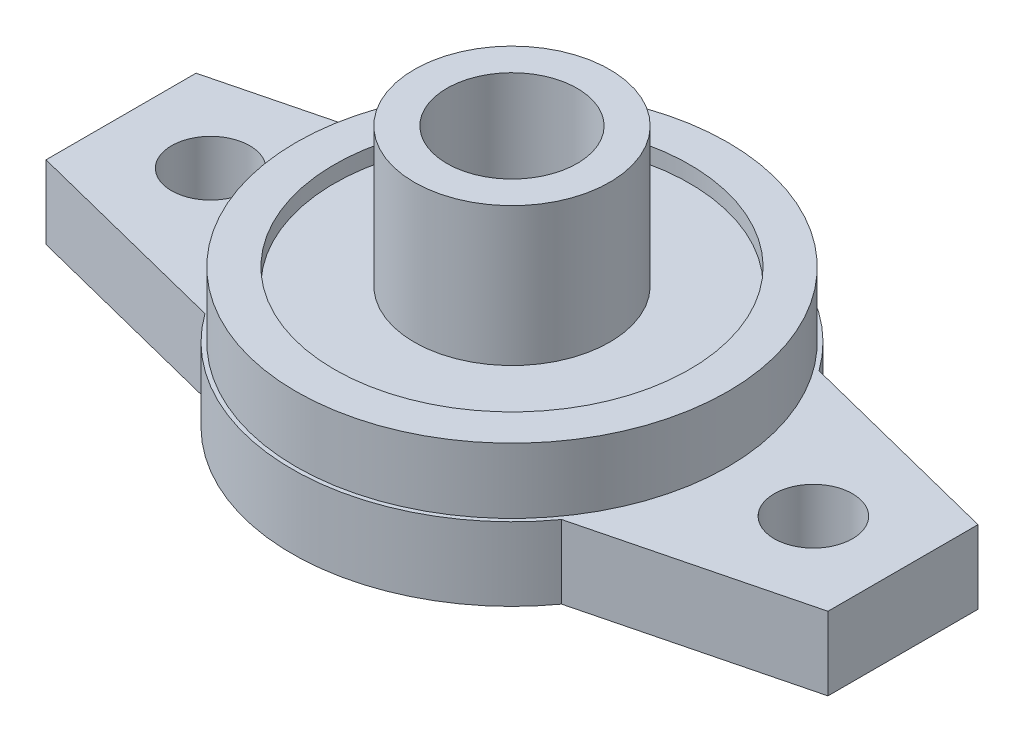
SolidWorks part; units mm, degrees
material "锌 AC41A 合金，作为铸件"
ref_plane "前视基准面" through (0, 0, 0) normal (0, 0, 1) x (1, 0, 0)
ref_plane "上视基准面" through (0, 0, 0) normal (0, 1, 0) x (1, 0, 0)
ref_plane "右视基准面" through (0, 0, 0) normal (1, 0, 0) x (0, 0, -1)
sketch "草图1" plane through (0, 0, 0) normal (0, 1, 0) x (1, 0, 0)
  line L0 (-643.3584, 0) -> (31524.5638, 0) construction
  line L1 (0, -643.3584) -> (0, 31524.5638) construction
  line L2 (-24, 4.605) -> (-24, -4.605)
  line L3 (-24, 4.605) -> (-10.9451, 7.9028)
  line L4 (-24, -4.605) -> (-10.9451, -7.9028)
  line L5 (24, -4.605) -> (10.9451, -7.9028)
  line L6 (24, 4.605) -> (10.9451, 7.9028)
  line L7 (24, 4.605) -> (24, -4.605)
  circle A0 centre (0, 0) radius 4
  circle A1 centre (0, 0) radius 13.5
  circle A2 centre (-18.5, 0) radius 2.4
  circle A3 centre (18.5, 0) radius 2.4
  point P13 (-24, 0)
  point P21 (24, 0)
  dimension "D1" = 4.8
  dimension "D2" = 27
  dimension "D3" = 8
  dimension "D4" = 24
  dimension "D5" = 18.5
extrude "凸台-拉伸1" add sketch "草图1" along normal blind 4.5 contours A1 L3 L2 L4 A2 | A1 A0 | A1 L5 L7 L6 A3
sketch "草图2" plane through (0, 4.5, 0) normal (0, 1, 0) x (1, 0, 0)
  circle A0 centre (0, 0) radius 13.25
  circle A1 centre (0, 0) radius 4 construction
  circle A2 centre (0, 0) radius 4
  dimension "D1" = 26.5
extrude "凸台-拉伸2" add sketch "草图2" along normal blind 4
sketch "草图3" plane through (0, 8.5, 0) normal (0, 1, 0) x (1, 0, 0)
  circle A0 centre (0, 0) radius 6
  circle A1 centre (0, 0) radius 4 construction
  circle A2 centre (0, 0) radius 4
  dimension "D1" = 12
extrude "凸台-拉伸3" add sketch "草图3" along normal blind 7.5
sketch "草图4" plane through (0, 8.5, 0) normal (0, 1, 0) x (1, 0, 0)
  circle A0 centre (0, 0) radius 6 construction
  circle A1 centre (0, 0) radius 6
  circle A2 centre (0, 0) radius 10.9
  circle A3 centre (0, 0) radius 13.25 construction
  dimension "D1" = 2.35
extrude "切除-拉伸1" cut sketch "草图4" against normal blind 1
